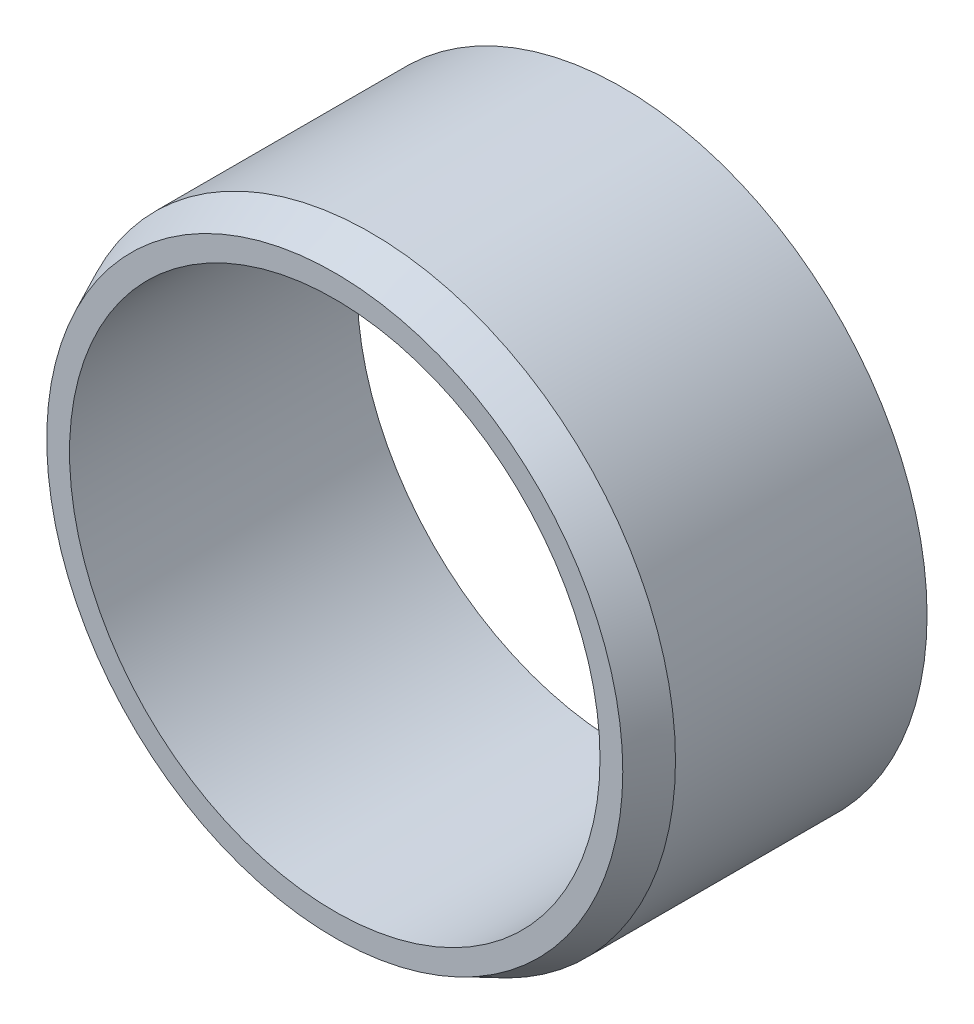
SolidWorks part; units mm, degrees
ref_plane "Front Plane" through (0, 0, 0) normal (0, 0, 1) x (1, 0, 0)
ref_plane "Top Plane" through (0, 0, 0) normal (0, 1, 0) x (1, 0, 0)
ref_plane "Right Plane" through (0, 0, 0) normal (1, 0, 0) x (0, 0, -1)
sketch "Sketch1" plane through (0, 0, 0) normal (0, 0, 1) x (1, 0, 0)
  circle A0 centre (0, 0) radius 9.225
  circle A1 centre (0, 0) radius 10.6
  dimension "D1" = 21.2
  dimension "D2" = 18.45
extrude "Boss-Extrude1" add sketch "Sketch1" along normal blind 10
chamfer "Chamfer1" distance 1.25 angle 25 1 edges at (10.6, 0, 10)
